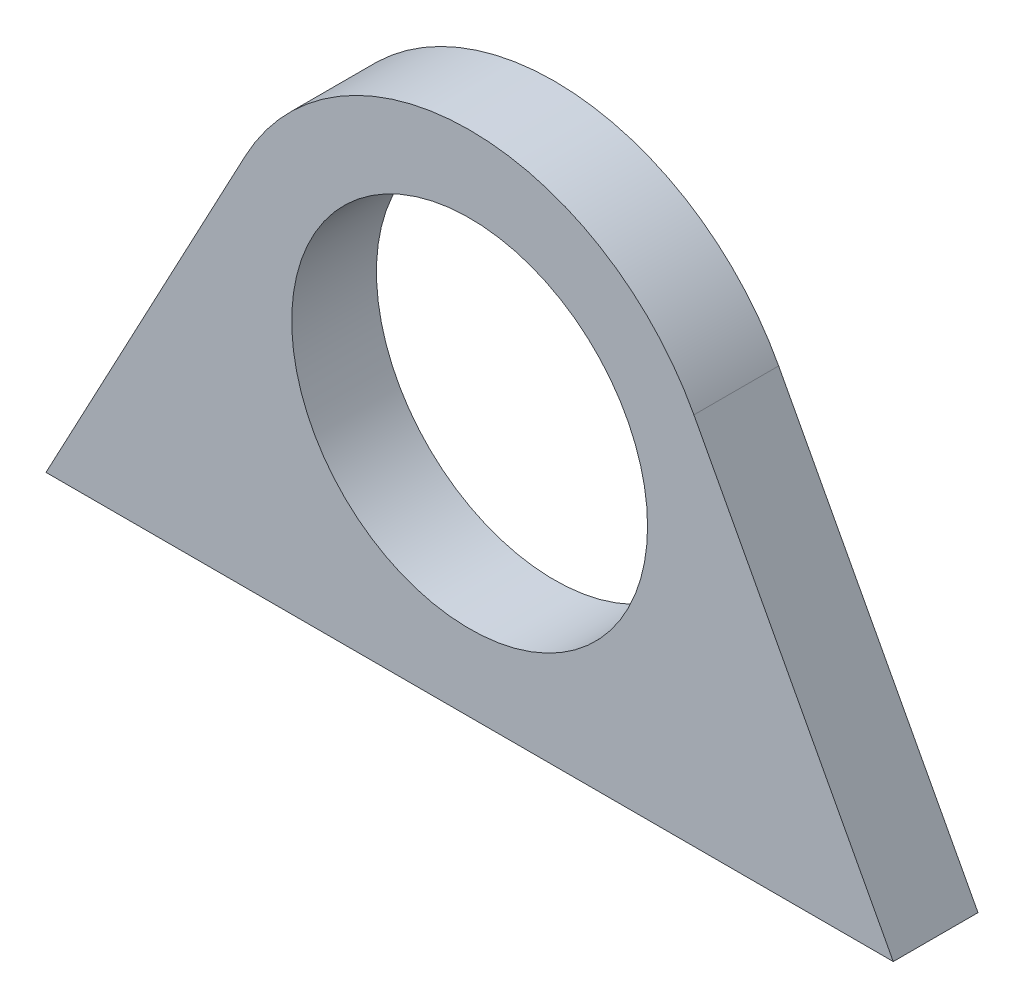
SolidWorks part; units mm, degrees
ref_plane "Front Plane" through (0, 0, 0) normal (0, 0, 1) x (1, 0, 0)
ref_plane "Top Plane" through (0, 0, 0) normal (0, 1, 0) x (1, 0, 0)
ref_plane "Right Plane" through (0, 0, 0) normal (1, 0, 0) x (0, 0, -1)
sketch "Sketch1" plane through (0, 0, 0) normal (0, 0, 1) x (1, 0, 0)
  line L0 (-25, -15) -> (25, -15)
  line L1 (-25, -15) -> (-13.2353, 7.0588)
  line L2 (25, -15) -> (13.2353, 7.0588)
  circle A0 centre (0, 0) radius 10.5
  arc A1 (13.2353, 7.0588) -> (-13.2353, 7.0588) centre (0, 0) ccw
  point P7 (0, -15)
  dimension "D1" = 21
  dimension "D2" = 30
  dimension "D3" = 50
extrude "Boss-Extrude1" add sketch "Sketch1" along normal blind 5
